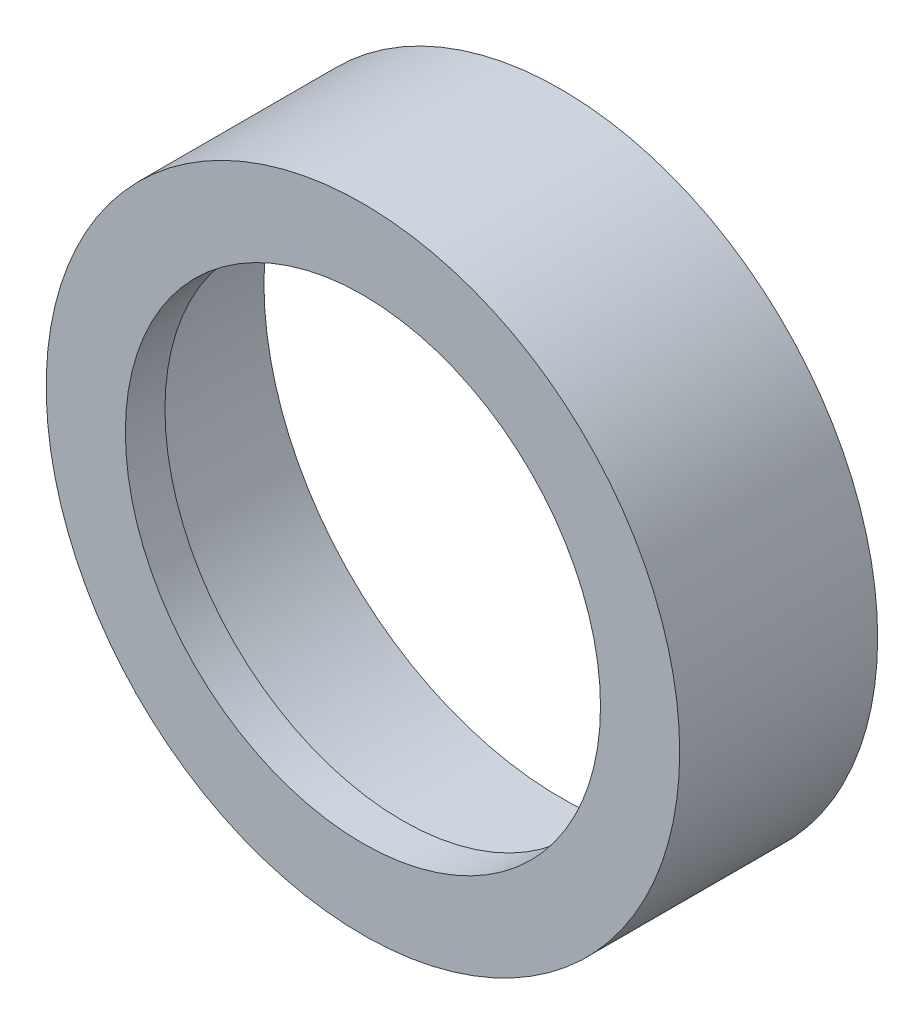
SolidWorks part; units mm, degrees
ref_plane "Front Plane" through (0, 0, 0) normal (0, 0, 1) x (1, 0, 0)
ref_plane "Top Plane" through (0, 0, 0) normal (0, 1, 0) x (1, 0, 0)
ref_plane "Right Plane" through (0, 0, 0) normal (1, 0, 0) x (0, 0, -1)
sketch "Sketch1" plane through (0, 0, 0) normal (0, 0, 1) x (1, 0, 0)
  circle A0 centre (0, 0) radius 40
  circle A1 centre (0, 0) radius 37.5
  dimension "D1" = 80
  dimension "D2" = 75
extrude "Boss-Extrude1" add sketch "Sketch1" against normal blind 25
sketch "Sketch2" plane through (0, 0, 0) normal (0, 0, -1) x (-1, 0, 0)
  circle A0 centre (0, 0) radius 30
  circle A1 centre (0, 0) radius 37.5
  circle A3 centre (0, 0) radius 37.5 construction
  dimension "D1" = 60
extrude "Boss-Extrude3" add sketch "Sketch2" along normal blind 5
